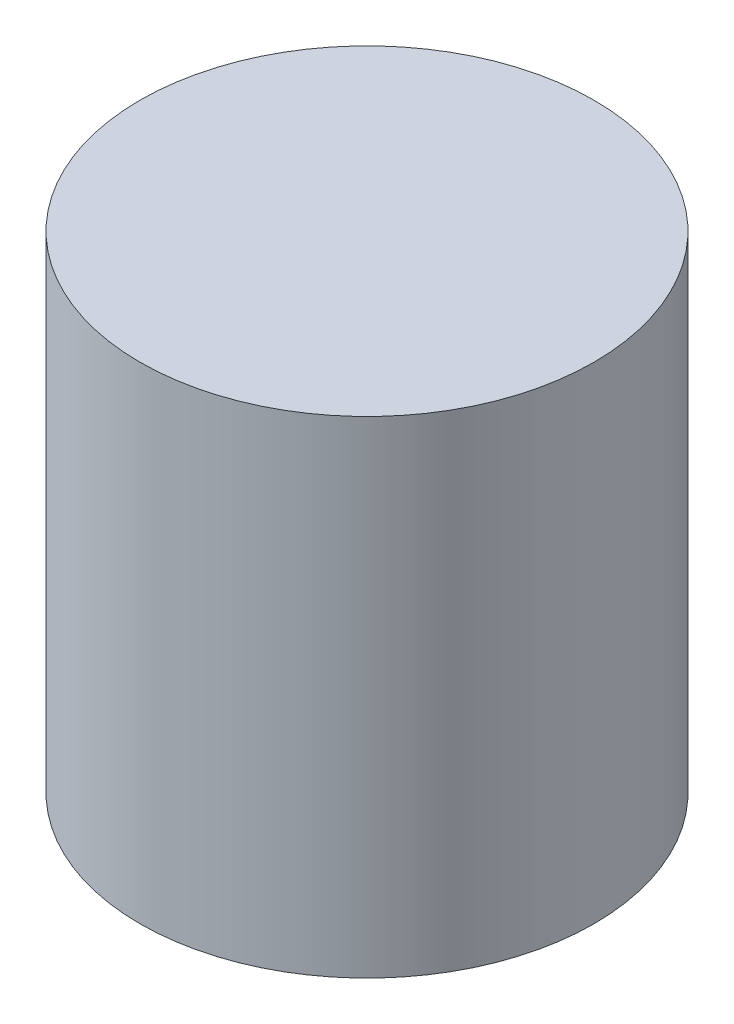
SolidWorks part; units mm, degrees
ref_plane "Front Plane" through (0, 0, 0) normal (0, 0, 1) x (1, 0, 0)
ref_plane "Top Plane" through (0, 0, 0) normal (0, 1, 0) x (1, 0, 0)
ref_plane "Right Plane" through (0, 0, 0) normal (1, 0, 0) x (0, 0, -1)
sketch "Sketch1" plane through (0, 0, 0) normal (0, 1, 0) x (1, 0, 0)
  circle A0 centre (0, 0) radius 14
  dimension "D1" = 28
extrude "Boss-Extrude1" add sketch "Sketch1" along normal blind 30
